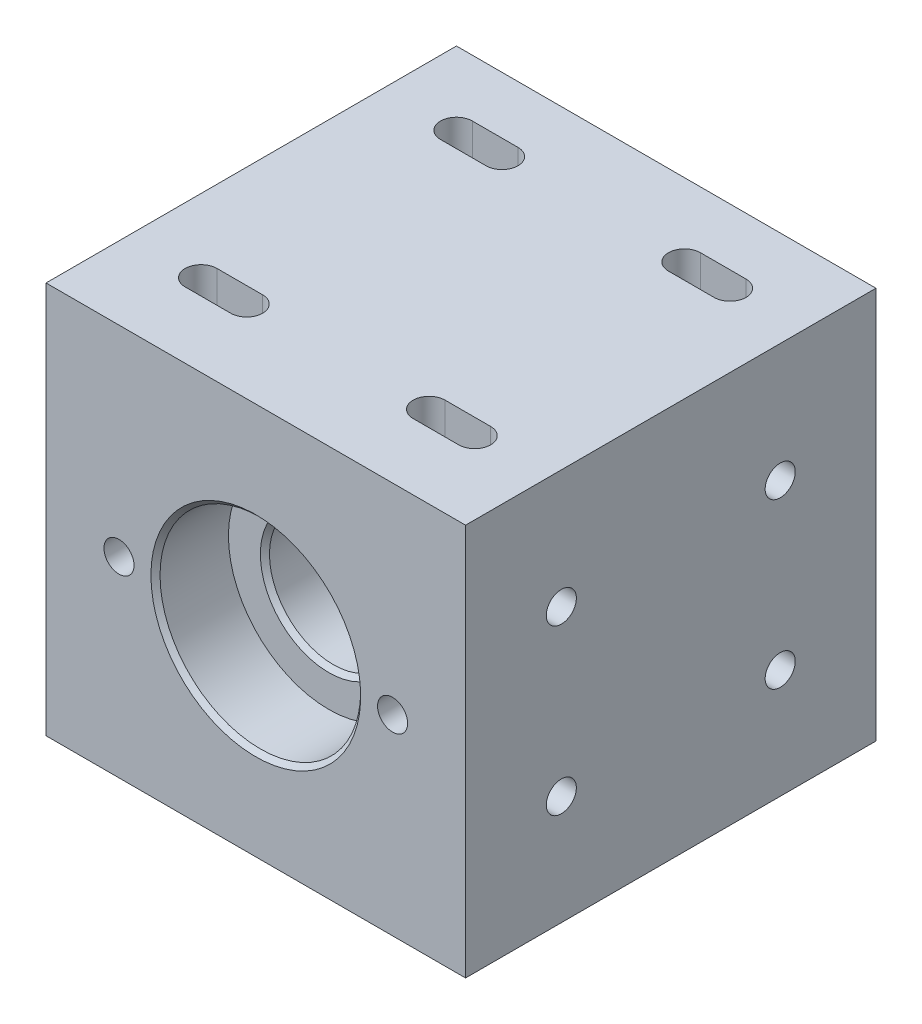
SolidWorks part; units mm, degrees
material "1060 Alloy"
ref_plane "Front Plane" through (0, 0, 0) normal (0, 0, 1) x (1, 0, 0)
ref_plane "Top Plane" through (0, 0, 0) normal (0, 1, 0) x (1, 0, 0)
ref_plane "Right Plane" through (0, 0, 0) normal (1, 0, 0) x (0, 0, -1)
sketch "Sketch1" plane through (0, 0, 0) normal (0, 0, 1) x (1, 0, 0)
  line L1 (23, 16) -> (-23, 16)
  line L2 (23, 16) -> (23, -16)
  line L3 (23, -16) -> (-23, -16)
  line L4 (-23, 16) -> (-23, -16)
  line L5 (0, -16) -> (0, 16) construction
  line L6 (23, 0) -> (-23, 0) construction
  circle A0 centre (0, 0) radius 7
  dimension "D1" = 14
  dimension "D2" = 46
  dimension "D3" = 32
extrude "Boss-Extrude1" add sketch "Sketch1" along normal mid plane 45
sketch "Sketch2" plane through (0, 0, 22.5) normal (0, 0, 1) x (1, 0, 0)
  circle A0 centre (0, 0) radius 11
  dimension "D1" = 22
extrude "Cut-Extrude1" cut sketch "Sketch2" against normal blind 8
sketch "Sketch3" plane through (0, 0, -22.5) normal (0, 0, -1) x (-1, 0, 0)
  circle A0 centre (0, 0) radius 11
  dimension "22" = 22
extrude "Cut-Extrude2" cut sketch "Sketch3" against normal blind 8
sketch "Sketch4" plane through (-23, 0, 0) normal (-1, 0, 0) x (0, 0, 1)
  circle A4 centre (12, -9) radius 1.65
  circle A5 centre (12, 9) radius 1.65
  circle A6 centre (-12, -9) radius 1.65
  circle A7 centre (-12, 9) radius 1.65
  dimension "D1" = 3.3
  dimension "D2" = 12
  dimension "D4" = 9
  dimension "D5" = 9
  dimension "D6" = 9
  dimension "D7" = 9
  dimension "12" = 12
extrude "Cut-Extrude3" cut sketch "Sketch4" against normal blind 10
mirror "Mirror1" about plane through (0, 0, 0) normal (1, 0, 0) of "Cut-Extrude3"
chamfer "Chamfer1" distance 0.5 angle 45 4 edges at (11, 0, 22.5) (7, 0, 14.5) (-7, 0, -14.5) (-11, 0, -22.5)
sketch "Sketch5" plane through (0, 16, 0) normal (0, 1, 0) x (1, 0, 0)
  line L0 (10, -13.5) -> (15, -13.5) construction
  line L1 (-10, -13.5) -> (-15, -13.5) construction
  line L2 (-10, -15.25) -> (-15, -15.25)
  line L3 (-15, -15.25) -> (-10, -15.25)
  line L4 (10, 14.5) -> (15, 14.5) construction
  line L5 (0, 0) -> (18.1655, 0) construction
  line L6 (0, 22.5) -> (0, 0) construction
  line L7 (10, 16.25) -> (15, 16.25)
  line L8 (23, 22.5) -> (-23, 22.5)
  line L9 (-23, 22.5) -> (-23, -22.5)
  line L10 (-23, -22.5) -> (23, -22.5)
  line L11 (23, -22.5) -> (23, 22.5)
  line L12 (-10, -11.75) -> (-15, -11.75)
  line L13 (-15, -11.75) -> (-10, -11.75)
  line L16 (15, 16.25) -> (10, 16.25)
  line L17 (10, 12.75) -> (15, 12.75)
  line L24 (15, 12.75) -> (10, 12.75)
  line L26 (15, -11.75) -> (10, -11.75)
  line L27 (10, -11.75) -> (15, -11.75)
  line L28 (15, -15.25) -> (10, -15.25)
  line L29 (10, -15.25) -> (15, -15.25)
  line L35 (-10, 14.5) -> (-15, 14.5) construction
  line L36 (-15, 12.75) -> (-10, 12.75)
  line L37 (-10, 12.75) -> (-15, 12.75)
  line L38 (-15, 16.25) -> (-10, 16.25)
  line L39 (-10, 16.25) -> (-15, 16.25)
  arc A0 (-15, -11.75) -> (-15, -15.25) centre (-15, -13.5) ccw
  arc A1 (-10, -15.25) -> (-10, -11.75) centre (-10, -13.5) ccw
  arc A8 (15, 12.75) -> (15, 16.25) centre (15, 14.5) ccw
  arc A9 (10, 16.25) -> (10, 12.75) centre (10, 14.5) ccw
  arc A16 (10, -15.25) -> (10, -11.75) centre (10, -13.5) cw
  arc A17 (15, -11.75) -> (15, -15.25) centre (15, -13.5) cw
  arc A20 (-10, 16.25) -> (-10, 12.75) centre (-10, 14.5) cw
  arc A21 (-15, 12.75) -> (-15, 16.25) centre (-15, 14.5) cw
  dimension "D4" = 1.75
  dimension "D12" = 1.75
  dimension "D14" = 9
  dimension "D15" = 10
  dimension "D1" = 45
  dimension "D2" = 46
  dimension "D3" = 23
  dimension "D5" = 5
  dimension "D6" = 8
  dimension "D7" = 10
  dimension "D8" = 22.5
  dimension "D9" = 23
  dimension "D10" = 22.5
  dimension "D11" = 23
  dimension "D13" = 5
extrude "Boss-Extrude2" add sketch "Sketch5" along normal blind 6
sketch "Sketch6" plane through (0, 0, -22.5) normal (0, 0, -1) x (-1, 0, 0)
  circle A0 centre (15, 0) radius 1.65
  circle A1 centre (-15, 0) radius 1.65
  dimension "D1" = 3.3
  dimension "D2" = 15
  dimension "D4" = 3.3
  dimension "D3" = 15
extrude "Cut-Extrude4" cut sketch "Sketch6" against normal blind 8
mirror "Mirror2" about plane through (0, 0, 0) normal (0, 0, 1) of "Cut-Extrude4"
sketch "Sketch8" plane through (0, -16, 0) normal (0, -1, 0) x (1, 0, 0)
  line L4 (-23, -22.5) -> (23, -22.5)
  line L5 (23, -22.5) -> (23, 22.5)
  line L6 (23, 22.5) -> (-23, 22.5)
  line L7 (-23, 22.5) -> (-23, -22.5)
  line L8 (-23, -22.5) -> (23, -22.5)
  line L9 (23, -22.5) -> (23, 22.5)
  line L10 (23, 22.5) -> (-23, 22.5)
  line L11 (-23, 22.5) -> (-23, -22.5)
  dimension "D1" = 0
extrude "Boss-Extrude3" add sketch "Sketch8" along normal blind 5
